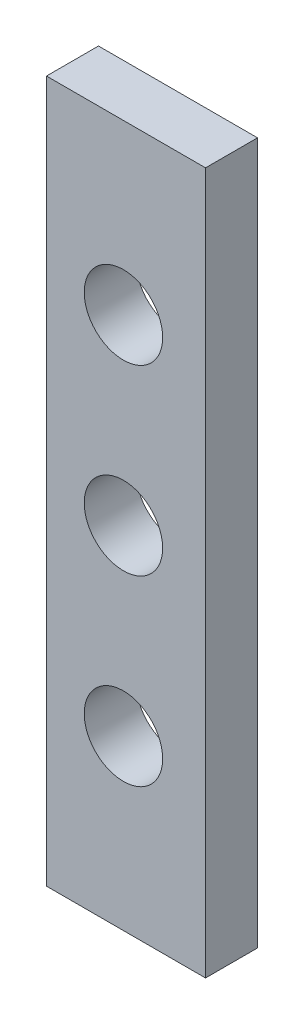
SolidWorks part; units mm, degrees
ref_plane "前视基准面" through (0, 0, 0) normal (0, 0, 1) x (1, 0, 0)
ref_plane "上视基准面" through (0, 0, 0) normal (0, 1, 0) x (1, 0, 0)
ref_plane "右视基准面" through (0, 0, 0) normal (1, 0, 0) x (0, 0, -1)
sketch "草图1" plane through (0, 0, 0) normal (0, 0, 1) x (1, 0, 0)
  line L0 (-121.2816, -66.5374) -> (-121.2816, -105) construction
  line L1 (-130, -105) -> (-121.2816, -105)
  line L2 (-130, -105) -> (-130, -66.5374)
  line L3 (-130, -66.5374) -> (-121.2816, -66.5374)
  line L4 (-121.2816, -105) -> (-121.2816, -66.5374)
  line L5 (-121.2816, -66.5374) -> (-121.2816, -105) construction
  point P3 (-121.2816, -66.8691)
  point P7 (0, 0)
extrude "凸台-拉伸1" add sketch "草图1" along normal offset from surface (2.85 mm away) 0.15
hole_wizard "打孔尺寸(%根据十字)槽沉头木螺钉的类型1" positions "草图2" profile "草图3" countersink size "M4" standard "GB"
sketch "草图2" plane through (40.4914, -131.0101, 7) normal (0, 0, 1) x (0, 1, 0)
  point P0 (35.2414, 166.273)
  point P3 (45.2414, 166.273)
  point P6 (55.2414, 166.273)
  point P9 (206.7788, 166.273)
  point P12 (216.7788, 166.273)
  point P15 (226.7788, 166.273)
sketch "草图3" plane through (-125.7816, -95.7687, 7) normal (1, 0, 0) x (0, -1, 0)
  line L0 (0, 0) -> (0, 20.2919)
  line L1 (0, 20.2919) -> (2.15, 19)
  line L2 (2.15, 19) -> (2.15, 1.85)
  line L3 (2.15, 1.85) -> (4, 0)
  line L4 (4, 0) -> (0, 0)
  line L5 (-2.15, 1.85) -> (-4, 0) construction
  line L6 (0, 20.2919) -> (-2.15, 19) construction
  line L7 (0, -6.35) -> (0, 107.95) construction
  dimension "孔直径" = 4.3
  dimension "孔深度" = 19
  dimension "近端锥形沉头孔直径" = 8
  dimension "近端锥形沉头孔角度" = 90
  dimension "导头角度" = 118
